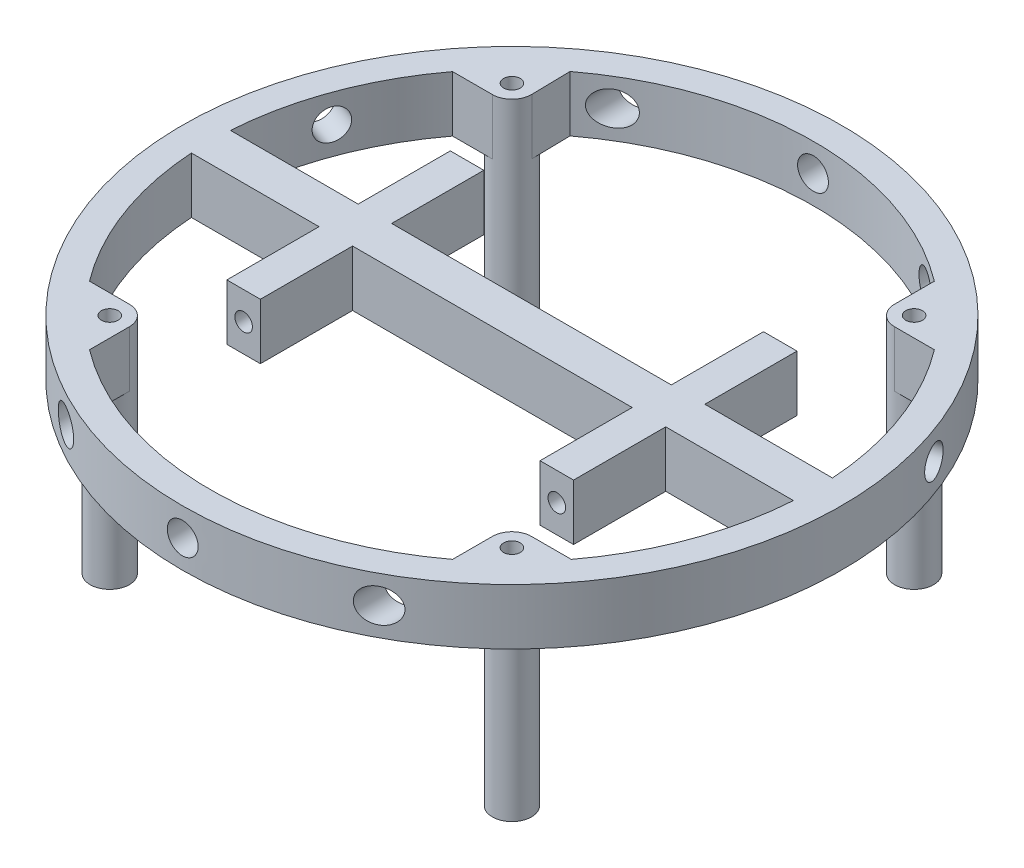
SolidWorks part; units mm, degrees
ref_plane "Front Plane" through (0, 0, 0) normal (0, 0, 1) x (1, 0, 0)
ref_plane "Top Plane" through (0, 0, 0) normal (0, 1, 0) x (1, 0, 0)
ref_plane "Right Plane" through (0, 0, 0) normal (1, 0, 0) x (0, 0, -1)
sketch "Sketch1" plane through (0, 0, 0) normal (0, 1, 0) x (1, 0, 0)
  line L1 (-84.9763, -6.8887) -> (-16.5405, -6.8887)
  line L6 (-84.9763, -11.3337) -> (-16.5405, -11.3337)
  circle A0 centre (-50.7584, -9.1112) radius 37.465
  circle A3 centre (-50.7584, -9.1112) radius 34.29
extrude "Boss-Extrude1" add sketch "Sketch1" along normal blind 6.35
sketch "Sketch2" plane through (0, 0, 17.0862) normal (0, 0, 1) x (1, 0, 0)
  circle A1 centre (-68.5584, 3.175) radius 1.25
  circle A2 centre (-32.9584, 3.175) radius 1.25
extrude "Cut-Extrude1" cut sketch "Sketch2" against normal blind 23.35
sketch "Sketch4" plane through (0, 6.35, 0) normal (0, 1, 0) x (1, 0, 0)
  line L1 (-73.4626, -34.8079) -> (-28.0542, -34.8079)
  line L5 (-69.2578, -37.9829) -> (-32.259, -37.9829)
  arc A0 (-84.9419, -11.8112) -> (-16.5749, -11.8112) centre (-50.7584, -9.1112) ccw construction
sketch "Sketch5" plane through (0, 6.35, 0) normal (0, 1, 0) x (1, 0, 0)
  line L3 (-83.3956, -19.6287) -> (-18.1212, -19.6287)
  line L7 (-29.3708, -35.9137) -> (-72.146, -35.9137)
  line L11 (-84.386, -15.8187) -> (-17.1308, -15.8187)
  line L12 (-66.2076, -39.7237) -> (-35.3092, -39.7237)
  arc A1 (-84.9419, -11.8112) -> (-16.5749, -11.8112) centre (-50.7584, -9.1112) ccw construction
sketch "Sketch6" plane through (0, 6.35, 0) normal (0, 1, 0) x (1, 0, 0)
  circle A0 centre (-69.6584, -17.8187) radius 0.8
  circle A1 centre (-31.8584, -17.8187) radius 0.8
  circle A2 centre (-31.8584, -37.8187) radius 0.8
  circle A3 centre (-69.6584, -37.8187) radius 0.8
sketch "Sketch7" plane through (0, 0, 0) normal (0, -1, 0) x (1, 0, 0)
  line L2 (-50.7584, 11.8112) -> (-50.7584, 6.4112)
  line L3 (-84.9419, 11.8112) -> (-16.5749, 11.8112) construction
  line L4 (-84.9419, 6.4112) -> (-16.5749, 6.4112) construction
  line L5 (-73.6184, -11.5263) -> (-78.1427, -11.5263)
  line L6 (-71.3959, -13.7488) -> (-71.4778, -18.2111)
  circle A2 centre (-50.7584, 9.1112) radius 34.29
  circle A5 centre (-73.6184, -13.7488) radius 1.05
  arc A7 (-71.3959, -13.7488) -> (-73.6184, -11.5263) centre (-73.6184, -13.7488) ccw
extrude "Boss-Extrude2" add sketch "Sketch7" against normal up to surface (6.35 mm away)
sketch "Sketch8" plane through (0, 0, 0) normal (0, -1, 0) x (1, 0, 0)
  line L2 (-27.8984, -11.5263) -> (-23.3741, -11.5263)
  line L3 (-30.1209, -13.7488) -> (-30.1209, -18.2731)
  line L4 (-30.1209, 31.9712) -> (-30.1209, 36.4955)
  line L5 (-27.8984, 29.7487) -> (-23.3741, 29.7487)
  line L6 (-71.3959, 31.9712) -> (-71.3959, 36.4955)
  line L7 (-73.6184, 29.7487) -> (-78.1427, 29.7487)
  arc A1 (-27.8984, -11.5263) -> (-30.1209, -13.7488) centre (-27.8984, -13.7488) ccw
  arc A3 (-30.1209, 31.9712) -> (-27.8984, 29.7487) centre (-27.8984, 31.9712) ccw
  circle A4 centre (-50.7584, 9.1112) radius 34.29
  circle A5 centre (-27.8984, -13.7488) radius 1.27
  circle A6 centre (-27.8984, 31.9712) radius 1.27
  circle A7 centre (-73.6184, 31.9712) radius 1.27
  circle A9 centre (-50.7584, 9.1112) radius 34.29 construction
  arc A10 (-73.6184, 29.7487) -> (-71.3959, 31.9712) centre (-73.6184, 31.9712) ccw
extrude "Boss-Extrude3" add sketch "Sketch8" against normal up to surface (6.35 mm away)
sketch "Sketch9" plane through (-50.7584, 361.355, 9.1112) normal (1, 0, -0.0007) x (0.0007, 0, 1)
  circle A0 centre (0, 358.1192) radius 1.6802
ref_plane "Plane1" through (-2.0289, 0, 15.4927) normal (0.1298, 0, -0.9915) x (0, -1, 0)
sketch "Sketch11" plane through (0.3113, 0, 2.3523) normal (-0.1312, 0, -0.9914) x (0, 1, 0)
  circle A0 centre (3.175, -62.7458) radius 1.6802
sketch "Sketch12" plane through (0, 0, 0) normal (0, -1, 0) x (1, 0, 0)
  line L0 (-50.7584, 9.1112) -> (-63.5722, -26.0944)
  line L1 (-50.7584, 9.1112) -> (-50.7584, -26.3992)
  circle A0 centre (-50.7584, 9.1112) radius 37.465 construction
  dimension "D1" = 20
ref_plane "Plane2" through (-63.5722, 0, -26.0944) normal (-0.342, 0, -0.9397) x (-0.9397, 0, 0.342)
sketch "Sketch13" plane through (-63.5722, 0, -26.0944) normal (-0.342, 0, -0.9397) x (-0.9397, 0, 0.342)
  circle A0 centre (0, 3.175) radius 1.6802
sketch "Sketch15" plane through (0, 0, 12.2862) normal (0, 0, 1) x (1, 0, 0)
  line L0 (-70.4634, 6.35) -> (-66.6534, 6.35)
  line L1 (-84.9011, 6.35) -> (-16.6157, 6.35) construction
  line L4 (-66.6534, 6.35) -> (-66.6534, 0)
  line L5 (-84.9011, 0) -> (-16.6157, 0) construction
  line L6 (-70.4634, 6.35) -> (-70.4634, 0)
  line L7 (-70.4634, 0) -> (-66.6534, 0)
  circle A0 centre (-68.5584, 3.175) radius 1.25
extrude "Boss-Extrude4" add sketch "Sketch15" along normal blind 9.525 and the other way blind 15.875
sketch "Sketch16" plane through (0, 0, 21.8112) normal (0, 0, 1) x (1, 0, 0)
  circle A1 centre (-68.5584, 3.175) radius 1.25
  circle A2 centre (-68.5584, 3.175) radius 1
extrude "Boss-Extrude5" add sketch "Sketch16" against normal up to surface (25.4 mm away) up to face at (-67.3084, 3.175, -3.5888)
sketch "Sketch17" plane through (0, 0, 11.3337) normal (0, 0, 1) x (1, 0, 0)
  circle A1 centre (-32.9584, 3.175) radius 1.25
  circle A2 centre (-32.9584, 3.175) radius 1
extrude "Boss-Extrude6" add sketch "Sketch17" along normal up to surface and the other way up to surface
sketch "Sketch18" plane through (0, 0, 12.2862) normal (0, 0, 1) x (1, 0, 0)
  line L0 (-34.8634, 6.35) -> (-31.0534, 6.35)
  line L1 (-66.6534, 6.35) -> (-16.6157, 6.35) construction
  line L4 (-31.0534, 6.35) -> (-31.0534, 0)
  line L5 (-66.6534, 0) -> (-16.6157, 0) construction
  line L6 (-31.0534, 0) -> (-34.8634, 0)
  line L7 (-34.8634, 0) -> (-34.8634, 6.35)
  circle A0 centre (-32.9584, 3.175) radius 0.9
extrude "Boss-Extrude7" add sketch "Sketch18" along normal blind 9.525 and the other way blind 15.875
sketch "Sketch20" plane through (0, 6.35, 0) normal (0, 1, 0) x (1, 0, 0)
  circle A1 centre (-73.6184, -31.9712) radius 1.27
  circle A3 centre (-27.8984, -31.9712) radius 1.27
  circle A5 centre (-27.8984, 13.7488) radius 1.27
  circle A6 centre (-73.6184, -31.9712) radius 1.05
  circle A7 centre (-27.8984, -31.9712) radius 1.05
  circle A8 centre (-27.8984, 13.7488) radius 1.05
extrude "Boss-Extrude8" add sketch "Sketch20" against normal up to surface (6.35 mm away) up to face at (-50.7635, 0, -5.007)
sketch "Sketch21" plane through (0, 6.35, 0) normal (0, 1, 0) x (1, 0, 0)
  circle A4 centre (-73.6184, 13.7488) radius 0.95
  circle A5 centre (-27.8984, 13.7488) radius 0.95
  circle A6 centre (-73.6184, -31.9712) radius 0.95
  circle A7 centre (-27.8984, -31.9712) radius 0.95
  circle A8 centre (-73.6184, -31.9712) radius 2.2225
  circle A9 centre (-27.8984, -31.9712) radius 2.2225
  circle A10 centre (-27.8984, 13.7488) radius 2.2225
  circle A11 centre (-73.6184, 13.7488) radius 2.2225
extrude "Boss-Extrude9" add sketch "Sketch21" against normal blind 25.4
sketch "Sketch22" plane through (0, 0, -3.5888) normal (0, 0, -1) x (-1, 0, 0)
  circle A0 centre (32.9584, 3.175) radius 1.905
  circle A1 centre (68.5584, 3.175) radius 1.905
extrude "Cut-Extrude4" cut sketch "Sketch22" along normal blind 37
sketch "Sketch23" plane through (0, 0, 21.8112) normal (0, 0, 1) x (1, 0, 0)
  circle A0 centre (-32.9584, 3.175) radius 1.905
  circle A1 centre (-68.5584, 3.175) radius 1.905
extrude "Cut-Extrude5" cut sketch "Sketch23" along normal blind 42
sketch "Sketch24" plane through (0, 0, 21.8112) normal (0, 0, 1) x (1, 0, 0)
  circle A0 centre (-68.5584, 3.175) radius 1
sketch "Sketch25" plane through (0, 0, 21.8112) normal (0, 0, 1) x (1, 0, 0)
  circle A0 centre (-32.9584, 3.175) radius 1
extrude "Cut-Extrude6" cut sketch "Sketch25" against normal blind 34
sketch "Sketch26" plane through (0, 6.35, 0) normal (0, 1, 0) x (-1, 0, 0)
  circle A0 centre (73.6184, 31.9712) radius 0.95
  circle A1 centre (73.6184, 31.9712) radius 1.05
  circle A2 centre (27.8984, 31.9712) radius 1.05
  circle A3 centre (27.8984, 31.9712) radius 0.95
  circle A4 centre (27.8984, -13.7488) radius 0.95
  circle A5 centre (27.8984, -13.7488) radius 1.05
  circle A6 centre (73.6184, -13.7488) radius 0.95
  circle A7 centre (73.6184, -13.7488) radius 1.05
extrude "Boss-Extrude10" add sketch "Sketch26" along normal up to surface (6.35 mm away)
sketch "Sketch27" plane through (0, 52.969, 0) normal (0, 0, 1) x (1, 0, 0)
  circle A0 centre (-50.7584, -49.794) radius 1.7526
extrude "Cut-Extrude7" cut sketch "Sketch27" along normal blind 12 and the other way blind 1 from offset 42
pattern_circular "CirPattern4" count 2 over 110 of "Cut-Extrude7"
sketch "Sketch28" plane through (0, 0, 6.8887) normal (0, 0, -1) x (-1, 0, 0)
  circle A0 centre (50.7789, 3.175) radius 1.7526
extrude "Cut-Extrude8" cut sketch "Sketch28" along normal blind 70
